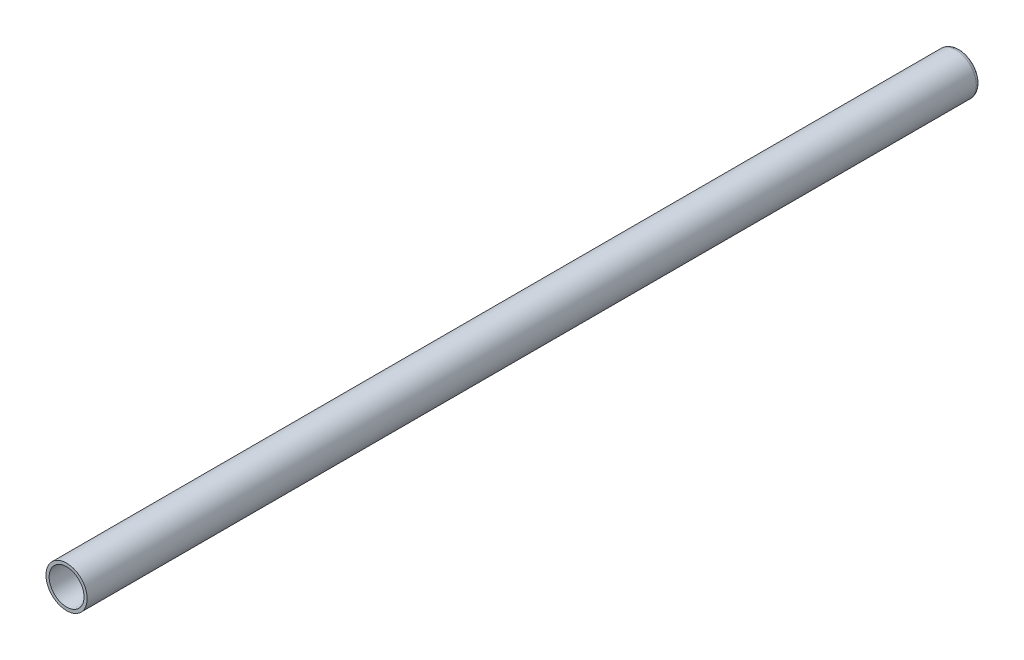
SolidWorks part; units mm, degrees
ref_plane "Alzado" through (0, 0, 0) normal (0, 0, 1) x (1, 0, 0)
ref_plane "Planta" through (0, 0, 0) normal (0, 1, 0) x (1, 0, 0)
ref_plane "Vista lateral" through (0, 0, 0) normal (1, 0, 0) x (0, 0, -1)
sketch "Croquis2" plane through (0, 0, 0) normal (0, 0, 1) x (1, 0, 0)
  circle A0 centre (0, 0) radius 15
  dimension "D1" = 30
extrude "Saliente-Extruir1" add sketch "Croquis2" against normal blind 650
sketch "Croquis3" plane through (0, 0, 0) normal (0, 0, 1) x (1, 0, 0)
  circle A0 centre (0, 0) radius 12.7
  dimension "D1" = 25.4
extrude "Cortar-Extruir1" cut sketch "Croquis3" against normal blind 640
fillet "Redondeo1" radius 3 1 edges at (15, 0, -650)
